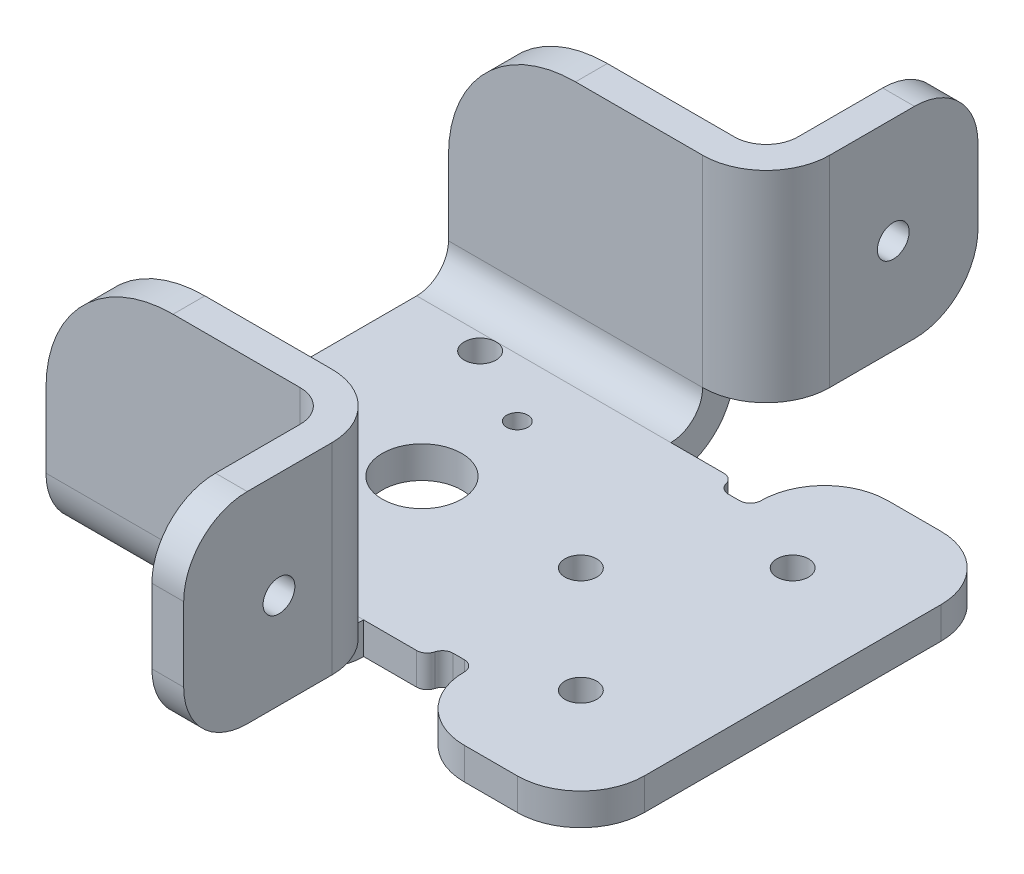
SolidWorks part; units mm, degrees
ref_plane "Front Plane" through (0, 0, 0) normal (0, 0, 1) x (1, 0, 0)
ref_plane "Top Plane" through (0, 0, 0) normal (0, 1, 0) x (1, 0, 0)
ref_plane "Right Plane" through (0, 0, 0) normal (1, 0, 0) x (0, 0, -1)
ref_plane "Plane1" through (0, 3, 0) normal (0, 1, 0) x (1, 0, 0)
sketch "Sketch1" plane through (0, 3, 0) normal (0, 1, 0) x (1, 0, 0)
  line L0 (-1, 14.5) -> (-30, 14.5)
  line L1 (-30, 14.5) -> (-30, -14.5)
  line L2 (-30, -14.5) -> (-1, -14.5)
  line L3 (0.9365, -13) -> (3.0839, -13)
  line L4 (9, -20) -> (20, -20)
  line L5 (20, -20) -> (20, 20)
  line L6 (20, 20) -> (9, 20)
  line L7 (3.0839, 13) -> (0.9365, 13)
  arc A0 (-1, -14.5) -> (-0.0318, -13.75) centre (-1, -13.5) ccw
  arc A1 (-0.0318, -13.75) -> (0.9365, -13) centre (0.9365, -14) cw
  arc A2 (3.0839, -13) -> (9, -20) centre (9, -14) ccw
  arc A3 (9, 20) -> (3.0839, 13) centre (9, 14) ccw
  arc A4 (0.9365, 13) -> (-0.0318, 13.75) centre (0.9365, 14) cw
  arc A5 (-0.0318, 13.75) -> (-1, 14.5) centre (-1, 13.5) ccw
extrude "Boss-Extrude1" add sketch "Sketch1" against normal blind 3
sketch "Sketch2" plane through (0, 0, -14.5) normal (0, 0, -1) x (-1, 0, 0)
  line L0 (6, 3) -> (30, 3)
  line L1 (30, 3) -> (30, 0)
  line L2 (30, 0) -> (6, 0)
  line L3 (6, 0) -> (6, 3)
extrude "Boss-Extrude2" add sketch "Sketch2" along normal blind 6
sketch "Sketch3" plane through (0, 3, 0) normal (0, 1, 0) x (-1, 0, 0)
  line L0 (6, -17.5) -> (30, -17.5)
  line L1 (30, -17.5) -> (30, -20.5)
  line L2 (30, -20.5) -> (6, -20.5)
  line L3 (6, -20.5) -> (6, -17.5)
extrude "Boss-Extrude3" add sketch "Sketch3" along normal blind 22
sketch "Sketch4" plane through (-6, 0, 0) normal (1, 0, 0) x (0, 0, -1)
  line L0 (20.5, 6) -> (17.5, 6)
  line L1 (17.5, 6) -> (17.5, 25)
  line L2 (17.5, 25) -> (20.5, 25)
  line L3 (20.5, 25) -> (20.5, 6)
extrude "Boss-Extrude4" add sketch "Sketch4" along normal blind 6
sketch "Sketch5" plane through (0, 0, -20.5) normal (0, 0, -1) x (-1, 0, 0)
  line L0 (0, 6) -> (0, 25)
  line L1 (0, 25) -> (3, 25)
  line L2 (3, 25) -> (3, 6)
  line L3 (3, 6) -> (0, 6)
extrude "Boss-Extrude5" add sketch "Sketch5" along normal blind 17
sketch "Sketch6" plane through (0, 0, 14.5) normal (0, 0, 1) x (1, 0, 0)
  line L0 (-30, 3) -> (-6, 3)
  line L1 (-6, 3) -> (-6, 0)
  line L2 (-6, 0) -> (-30, 0)
  line L3 (-30, 0) -> (-30, 3)
extrude "Boss-Extrude6" add sketch "Sketch6" along normal blind 6
sketch "Sketch7" plane through (0, 3, 0) normal (0, 1, 0) x (-1, 0, 0)
  line L0 (6, 17.5) -> (6, 20.5)
  line L1 (6, 20.5) -> (30, 20.5)
  line L2 (30, 20.5) -> (30, 17.5)
  line L3 (30, 17.5) -> (6, 17.5)
extrude "Boss-Extrude7" add sketch "Sketch7" along normal blind 22
sketch "Sketch8" plane through (-6, 0, 0) normal (1, 0, 0) x (0, 0, -1)
  line L0 (-20.5, 6) -> (-20.5, 25)
  line L1 (-20.5, 25) -> (-17.5, 25)
  line L2 (-17.5, 25) -> (-17.5, 6)
  line L3 (-17.5, 6) -> (-20.5, 6)
extrude "Boss-Extrude8" add sketch "Sketch8" along normal blind 6
sketch "Sketch9" plane through (0, 0, 20.5) normal (0, 0, 1) x (1, 0, 0)
  line L0 (-3, 6) -> (-3, 25)
  line L1 (-3, 25) -> (0, 25)
  line L2 (0, 25) -> (0, 6)
  line L3 (0, 6) -> (-3, 6)
extrude "Boss-Extrude9" add sketch "Sketch9" along normal blind 17
hole_wizard "Ø2.0 (2) Diameter Hole1" positions "Sketch11" profile "Sketch10" hole size "Ø2.0" standard "ANSI Metric"
sketch "Sketch11" plane through (0, 0, 0) normal (0, -1, 0) x (-1, 0, 0)
  point P0 (15, -9)
  point P1 (15, 9)
sketch "Sketch10" plane through (-15, 0, 9) normal (1, 0, 0) x (0, 0, -1)
  line L0 (0, 0) -> (0, 25)
  line L1 (0, 25) -> (1, 25)
  line L2 (1, 25) -> (1, 0)
  line L5 (1, 0) -> (0, 0)
  line L11 (0, -6.35) -> (0, 107.95) construction
  dimension "Thru Hole Dia." = 2
  dimension "Thru Hole Depth" = 25
hole_wizard "Ø7.5 (7.5) Diameter Hole1" positions "Sketch13" profile "Sketch12" hole size "Ø7.5" standard "ANSI Metric"
sketch "Sketch13" plane through (0, 0, 0) normal (0, -1, 0) x (-1, 0, 0)
  point P0 (15, 0)
sketch "Sketch12" plane through (-15, 0, 0) normal (1, 0, 0) x (0, 0, -1)
  line L0 (0, 0) -> (0, 25)
  line L1 (0, 25) -> (3.75, 25)
  line L2 (3.75, 25) -> (3.75, 0)
  line L5 (3.75, 0) -> (0, 0)
  line L11 (0, -6.35) -> (0, 107.95) construction
  dimension "Thru Hole Dia." = 7.5
  dimension "Thru Hole Depth" = 25
hole_wizard "Ø3.0 (3) Diameter Hole1" positions "Sketch15" profile "Sketch14" hole size "Ø3.0" standard "ANSI Metric"
sketch "Sketch15" plane through (0, 3, 0) normal (0, 1, 0) x (1, 0, 0)
  point P0 (10, -10)
  point P1 (10, 10)
sketch "Sketch14" plane through (10, 3, 10) normal (1, 0, 0) x (0, 0, 1)
  line L0 (0, 0) -> (0, 3)
  line L1 (0, 3) -> (1.5, 3)
  line L2 (1.5, 3) -> (1.5, 0)
  line L5 (1.5, 0) -> (0, 0)
  line L11 (0, -6.35) -> (0, 107.95) construction
  dimension "Thru Hole Dia." = 3
  dimension "Thru Hole Depth" = 3
hole_wizard "Ø3.0 (3) Diameter Hole2" positions "Sketch17" profile "Sketch16" hole size "Ø3.0" standard "ANSI Metric"
sketch "Sketch17" plane through (-3, 0, 0) normal (-1, 0, 0) x (0, 0, 1)
  point P0 (28.5, 15)
  point P1 (-29.5, 15)
sketch "Sketch16" plane through (-3, 15, 28.5) normal (0, 1, 0) x (0, 0, 1)
  line L0 (0, 0) -> (0, 23)
  line L1 (0, 23) -> (1.5, 23)
  line L2 (1.5, 23) -> (1.5, 0)
  line L5 (1.5, 0) -> (0, 0)
  line L11 (0, -6.35) -> (0, 107.95) construction
  dimension "Thru Hole Dia." = 3
  dimension "Thru Hole Depth" = 23
fillet "Fillet1" radius 1 2 edges at (3.0839, 1.5, 13) (3.0839, 1.5, -13)
fillet "Fillet2" radius 3 4 edges at (-18, 3, -17.5) (-3, 15.5, 20.5) (-18, 3, 17.5) (-3, 15.5, -20.5)
fillet "Fillet3" radius 6 10 edges at (0, 15.5, 17.5) (20, 1.5, -20) (-18, 0, 20.5) (-18, 0, -20.5) (-1.5, 25, 37.5) (20, 1.5, 20) (0, 15.5, -17.5) (-1.5, 6, -37.5) (-1.5, 6, 37.5) (-1.5, 25, -37.5)
fillet "Fillet4" radius 12 2 edges at (-30, 25, 19) (-30, 25, -19)
hole_wizard "Hole1" positions "Sketch19" profile "Sketch18" legacy
sketch "Sketch19" plane through (0, 0, 0) normal (0, -1, 0) x (-1, 0, 0)
  point P0 (0, 0)
  point P1 (22.5, -12.9904)
  point P2 (22.5, 12.9904)
sketch "Sketch18" plane through (0, 0, 0) normal (1, 0, 0) x (0, 0, -1)
  line L0 (0, 0) -> (0, 3.9013)
  line L1 (0, 3.9013) -> (1.5, 3)
  line L2 (1.5, 3) -> (1.5, 0)
  line L4 (1.5, 0) -> (0, 0)
  line L6 (0, 3.9013) -> (-1.5, 3) construction
  line L7 (0, -4.2442) -> (0, 117.3081) construction
  dimension "Diameter" = 3
  dimension "Depth" = 3
  dimension "Drill Angle" = 118
